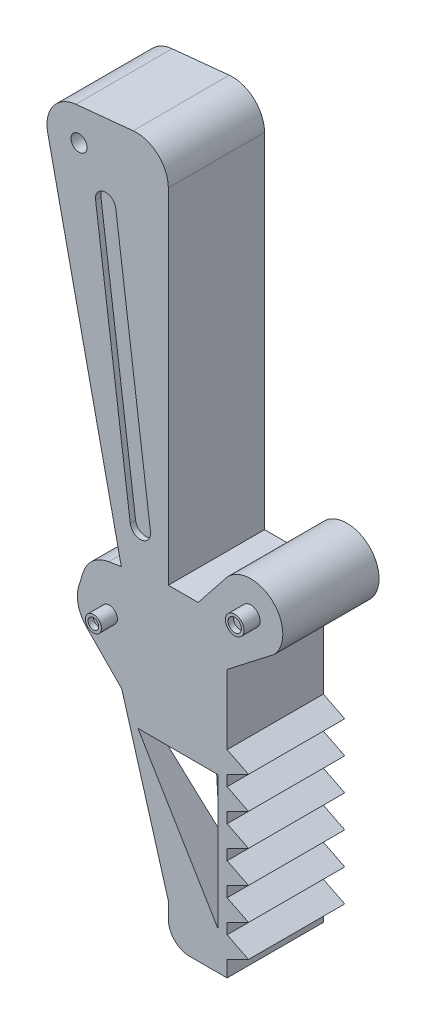
SolidWorks part; units mm, degrees
ref_plane "Front Plane" through (0, 0, 0) normal (0, 0, 1) x (1, 0, 0)
ref_plane "Top Plane" through (0, 0, 0) normal (0, 1, 0) x (1, 0, 0)
ref_plane "Right Plane" through (0, 0, 0) normal (1, 0, 0) x (0, 0, -1)
sketch "Sketch1" plane through (0, 0, 0) normal (0, 0, 1) x (1, 0, 0)
  line L0 (0, 0) -> (-122.3375, 0) construction
  line L1 (0, 0) -> (-24, -2.3891)
  line L2 (-24, -2.3891) -> (-8.7943, -72.3891)
  line L4 (0, -71) -> (0, 0)
  line L5 (0, -71) -> (-8.7943, -72.3891)
  line L6 (-8.7943, -72.3891) -> (-14.8163, -73.3404)
  line L7 (-14.8163, -73.3404) -> (-17.8301, -82.8754)
  line L8 (-17.8301, -82.8754) -> (-8.7118, -92.1413)
  line L9 (-8.7118, -92.1413) -> (0, -122.1413)
  line L10 (0, -122.1413) -> (0, -129.1413)
  line L11 (0, -129.1413) -> (11, -129.1413)
  line L12 (11, -129.1413) -> (11, -79.1413)
  line L13 (0, -71) -> (5.5849, -71)
  line L14 (5.5849, -71) -> (11, -64.1734)
  line L15 (11, -79.1413) -> (19.8415, -72.2868)
  arc A0 (11, -64.1734) -> (19.8415, -72.2868) centre (15.4208, -68.2301) cw
  dimension "D5" = 6
  dimension "D1" = 70
  dimension "D2" = 71
  dimension "D3" = 24
  dimension "D4" = 15
  dimension "D6" = 13
  dimension "D7" = 30
  dimension "D8" = 7
  dimension "D9" = 11
  dimension "D10" = 50
  dimension "D12" = 10
extrude "Boss-Extrude1" add sketch "Sketch1" along normal blind 18 contours L5 L4 L1 L2 | A0 L14 L13 L5 L6 L7 L8 L9 L10 L11 L12 L15
fillet "Fillet1" radius 6 2 edges at (-24, -2.3891, 9) (0, 0, 9)
fillet "Fillet2" radius 6 2 edges at (-17.8301, -82.8754, 9) (-14.8163, -73.3404, 9)
fillet "Fillet3" radius 4 1 edges at (0, -129.1413, 9)
sketch "Sketch2" plane through (0, 0, 0) normal (0, 0, -1) x (-1, 0, 0)
  line L0 (-11, -129.1413) -> (-11, -124.1413) construction
  line L1 (-11, -129.1413) -> (-11, -79.1413) construction
  line L2 (-11, -126.1413) -> (-11, -122.1413)
  line L3 (-11, -124.1413) -> (-15, -124.1413) construction
  line L4 (-11, -122.1413) -> (-15, -124.1413)
  line L5 (-11, -126.1413) -> (-15, -124.1413)
  point P8 (-11, -124.1413)
  dimension "D1" = 5
  dimension "D2" = 4
  dimension "D3" = 4
extrude "Boss-Extrude2" add sketch "Sketch2" against normal up to vertex (18 mm away)
pattern_linear "LPattern1" count 6 spacing 6 along (0, 1, 0) of "Boss-Extrude2"
sketch "Sketch3" plane through (0, 0, 18) normal (0, 0, 1) x (1, 0, 0)
  line L0 (9.3074, -122.0416) -> (9.3074, -97.0416)
  line L1 (9.3074, -97.0416) -> (-5.6926, -97.0416)
  line L2 (-5.6926, -97.0416) -> (9.3074, -122.0416)
  dimension "D1" = 15
  dimension "D2" = 25
extrude "Cut-Extrude1" cut sketch "Sketch3" against normal blind 24
sketch "Sketch4" plane through (-32.7105, -9.4989, 0) normal (-0.9603, -0.2789, 0) x (0, 0, 1)
  line L0 (3, -93.0564) -> (15, -93.0564)
  line L1 (15, -93.0564) -> (11, -112.2958)
  line L2 (11, -112.2958) -> (7, -112.2958)
  line L3 (7, -112.2958) -> (3, -93.0564)
  line L4 (18, -86.0564) -> (0, -86.0564) construction
  line L5 (18, -117.2958) -> (0, -117.2958) construction
  line L6 (18, -86.0564) -> (18, -117.2958) construction
  line L7 (0, -86.0564) -> (0, -117.2958) construction
  dimension "D1" = 7
  dimension "D2" = 5
  dimension "D3" = 3
  dimension "D4" = 3
  dimension "D5" = 7
  dimension "D6" = 7
extrude "Cut-Extrude2" cut sketch "Sketch4" against normal blind 7
sketch "Sketch5" plane through (0, 0, 18) normal (0, 0, 1) x (1, 0, 0)
  circle A0 centre (-16.708, -7.6929) radius 1.5
  dimension "D1" = 3
extrude "Cut-Extrude3" cut sketch "Sketch5" against normal blind 24 and the other way blind 1
sketch "Sketch6" plane through (0, 0, 18) normal (0, 0, 1) x (1, 0, 0)
  circle A0 centre (-11.0208, -81.2407) radius 1.5
  circle A1 centre (15.4208, -68.2301) radius 1.75
  dimension "D1" = 3
  dimension "D2" = 3.5
extrude "Boss-Extrude3" add sketch "Sketch6" along normal blind 3
sketch "Sketch7" plane through (0, 0, 21) normal (0, 0, 1) x (1, 0, 0)
  circle A2 centre (-11.0208, -81.2407) radius 1
  circle A3 centre (-11.0208, -81.2407) radius 1
  dimension "D1" = 0.5
extrude "Cut-Extrude4" cut sketch "Sketch7" against normal blind 1
sketch "Sketch8" plane through (0, 0, 21) normal (0, 0, 1) x (1, 0, 0)
  circle A2 centre (15.4208, -68.2301) radius 1.25
  circle A3 centre (15.4208, -68.2301) radius 1.25
  dimension "D1" = 0.5
extrude "Cut-Extrude5" cut sketch "Sketch8" against normal blind 1
sketch "Sketch9" plane through (0, 0, 18) normal (0, 0, 1) x (1, 0, 0)
  line L0 (-11.7221, -15.1114) -> (-5.23, -64.2939) construction
  line L1 (-9.8287, -14.8614) -> (-3.3366, -64.044)
  line L2 (-13.6155, -15.3613) -> (-7.1234, -64.5439)
  arc A0 (-9.8287, -14.8614) -> (-13.6155, -15.3613) centre (-11.7221, -15.1114) ccw
  arc A1 (-7.1234, -64.5439) -> (-3.3366, -64.044) centre (-5.23, -64.2939) ccw
  point P2 (-8.476, -39.7026)
extrude "Cut-Extrude6" cut sketch "Sketch9" against normal blind 1
ref_plane "Plane1" through (0, 0, 9) normal (0, 0, 1) x (1, 0, 0)
mirror "Mirror1" about plane through (0, 0, 9) normal (0, 0, 1) of "Cut-Extrude5", "Cut-Extrude6", "Cut-Extrude4", "Boss-Extrude3"
